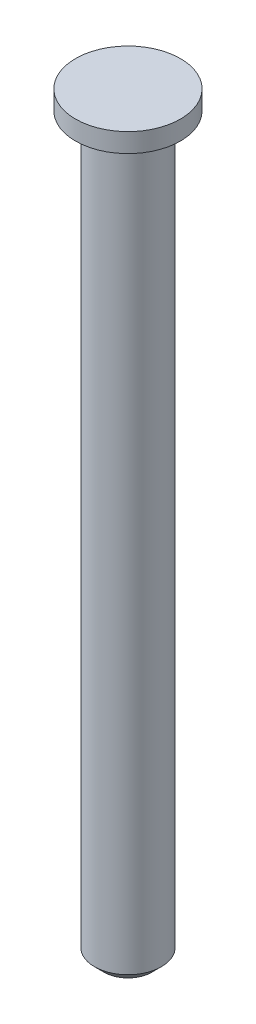
SolidWorks part; units mm, degrees
material "Простая углеродистая сталь"
ref_plane "Спереди" through (0, 0, 0) normal (0, 0, 1) x (1, 0, 0)
ref_plane "Сверху" through (0, 0, 0) normal (0, 1, 0) x (1, 0, 0)
ref_plane "Справа" through (0, 0, 0) normal (1, 0, 0) x (0, 0, -1)
sketch "Эскиз1" plane through (0, 0, 0) normal (0, 0, 1) x (1, 0, 0)
  line L0 (0, 68.7168) -> (0, -65.6627) construction
  line L1 (0, 39.5) -> (-5.5, 39.5)
  line L2 (-5.5, 39.5) -> (-5.5, 37.5)
  line L3 (-5.5, 37.5) -> (-3.5, 37.5)
  line L4 (-3.5, 37.5) -> (-3.5, -39.5)
  line L5 (-3.5, -39.5) -> (0, -39.5)
  line L6 (0, -39.5) -> (0, 39.5)
  dimension "D1" = 77
  dimension "D2" = 2
  dimension "D3" = 7
  dimension "D4" = 11
revolve "Повернуть1" add sketch "Эскиз1" angle 360 about L0
chamfer "Фаска1" distance 1 angle 45 1 edges at (0, -39.5, 3.5)
